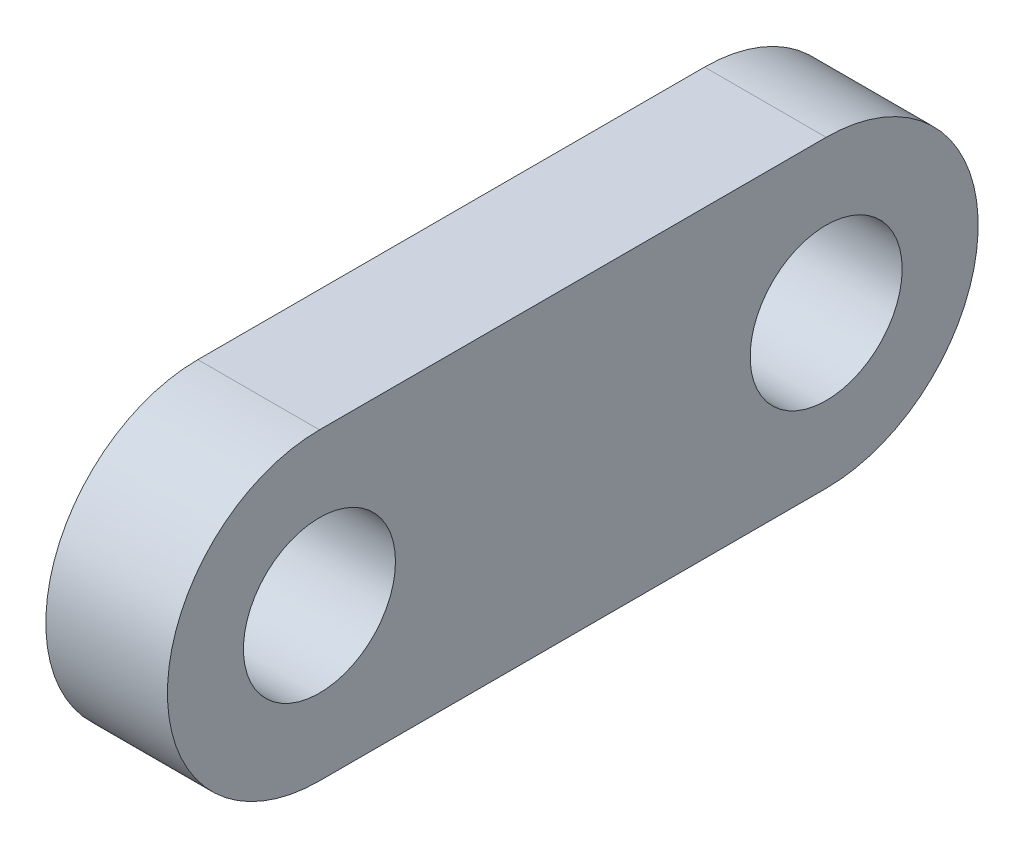
SolidWorks part; units mm, degrees
ref_plane "Alzado" through (0, 0, 0) normal (0, 0, 1) x (1, 0, 0)
ref_plane "Planta" through (0, 0, 0) normal (0, 1, 0) x (1, 0, 0)
ref_plane "Vista lateral" through (0, 0, 0) normal (1, 0, 0) x (0, 0, -1)
sketch "Croquis1" plane through (0, 0, 0) normal (1, 0, 0) x (0, 0, -1)
  line L0 (0, 0) -> (50, 0) construction
  line L1 (0, 15) -> (50, 15)
  line L2 (0, -15) -> (50, -15)
  arc A0 (0, 15) -> (0, -15) centre (0, 0) ccw
  arc A1 (50, -15) -> (50, 15) centre (50, 0) ccw
  circle A2 centre (0, 0) radius 7.5
  circle A3 centre (50, 0) radius 7.5
  point P3 (25, 0)
  dimension "D3" = 15
  dimension "D1" = 50
  dimension "D2" = 30
extrude "Saliente-Extruir1" add sketch "Croquis1" along normal blind 12
